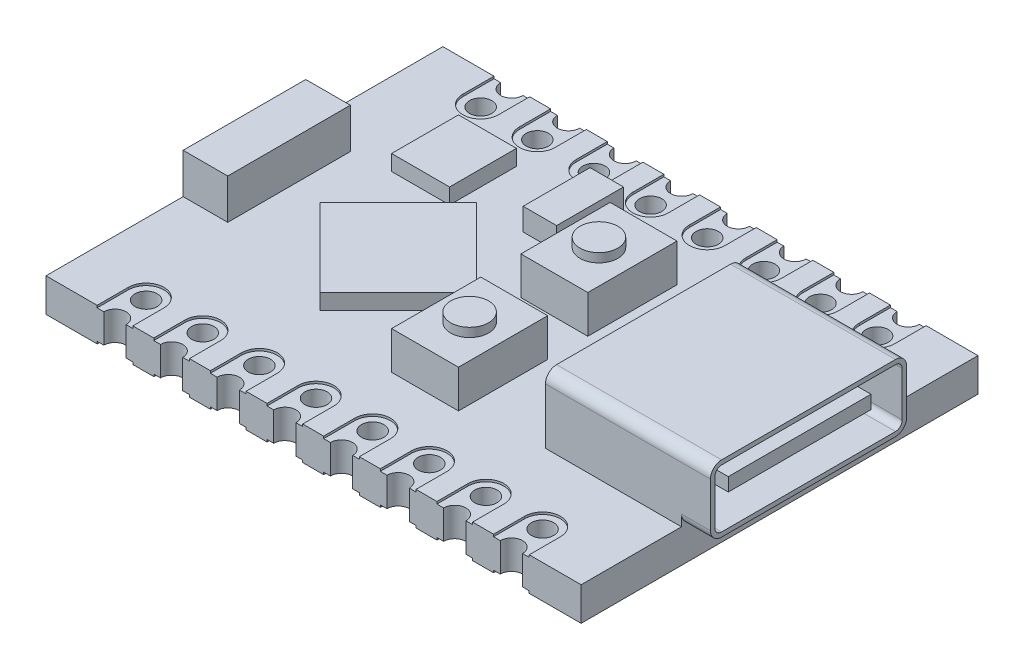
SolidWorks part; units mm, degrees
ref_plane "Front Plane" through (0, 0, 0) normal (0, 0, 1) x (1, 0, 0)
ref_plane "Top Plane" through (0, 0, 0) normal (0, 1, 0) x (1, 0, 0)
ref_plane "Right Plane" through (0, 0, 0) normal (1, 0, 0) x (0, 0, -1)
sketch "Sketch1" plane through (0, 0, 0) normal (0, 1, 0) x (1, 0, 0)
  line L1 (0, 0) -> (24, 0)
  line L2 (0, 0) -> (0, 17.8)
  line L3 (0, 17.8) -> (24, 17.8)
  line L4 (24, 0) -> (24, 17.8)
  dimension "D1" = 24
  dimension "D2" = 17.8
sketch "Sketch2" plane through (0, 0, 0) normal (0, 1, 0) x (1, 0, 0)
  line L0 (0, 0) -> (0, 17.8) construction
  line L1 (0, 0) -> (0, 17.8)
  line L2 (0, 17.8) -> (24, 17.8) construction
  line L3 (0, 17.8) -> (24, 17.8)
  line L4 (24, 0) -> (24, 17.8) construction
  line L5 (24, 0) -> (24, 17.8)
  line L6 (0, 0) -> (24, 0) construction
  line L7 (0, 0) -> (24, 0)
extrude "Boss-Extrude1" add sketch "Sketch2" against normal blind 1.5
sketch "Sketch3" plane through (0, 0, 0) normal (0, 1, 0) x (1, 0, 0)
  line L0 (0, 8.9) -> (24, 8.9) construction
  line L1 (0, 0) -> (0, 17.8) construction
  line L2 (24, 0) -> (24, 17.8) construction
  line L4 (2, 11.65) -> (0, 11.65)
  line L5 (2, 11.65) -> (2, 6.15)
  line L6 (2, 6.15) -> (0, 6.15)
  line L7 (0, 11.65) -> (0, 6.15)
  line L8 (2, 11.65) -> (0, 6.15) construction
  line L9 (2, 6.15) -> (0, 11.65) construction
  point P6 (1, 8.9)
  dimension "D1" = 5.5
  dimension "D2" = 2
extrude "Boss-Extrude2" add sketch "Sketch3" along normal blind 1.8
sketch "Sketch4" plane through (0, 0, 0) normal (0, 1, 0) x (1, 0, 0)
  line L0 (2, 6.15) -> (2, 11.65) construction
  line L3 (4, 8.3) -> (7.5, 11.8)
  line L4 (4, 8.3) -> (7.5, 4.8)
  line L5 (7.5, 11.8) -> (11, 8.3)
  line L6 (7.5, 4.8) -> (11, 8.3)
  line L7 (0, 17.8) -> (24, 17.8) construction
  dimension "D1" = 6
  dimension "D2" = 7
  dimension "D3" = 7
  dimension "D4" = 2
extrude "Boss-Extrude3" add sketch "Sketch4" along normal blind 0.7
sketch "Sketch5" plane through (0, 0, 0) normal (0, 1, 0) x (1, 0, 0)
  line L0 (0, 17.8) -> (24, 17.8) construction
  line L1 (3.7, 14.8) -> (6.3, 14.8)
  line L2 (3.7, 14.8) -> (3.7, 11.8)
  line L3 (3.7, 11.8) -> (6.3, 11.8)
  line L4 (6.3, 14.8) -> (6.3, 11.8)
  line L5 (0, 0) -> (0, 17.8) construction
  dimension "D1" = 2.6
  dimension "D2" = 3
  dimension "D3" = 3
  dimension "D4" = 3.7
extrude "Boss-Extrude4" add sketch "Sketch5" along normal blind 0.7
sketch "Sketch6" plane through (0, 0, 0) normal (0, 1, 0) x (1, 0, 0)
  line L0 (0, 0) -> (0, 17.8) construction
  line L1 (9, 15.4) -> (10.5, 15.4)
  line L2 (9, 15.4) -> (9, 12.4)
  line L3 (9, 12.4) -> (10.5, 12.4)
  line L4 (10.5, 15.4) -> (10.5, 12.4)
  line L5 (0, 17.8) -> (24, 17.8) construction
  dimension "D1" = 1.5
  dimension "D2" = 3
  dimension "D3" = 9
  dimension "D4" = 2.4
extrude "Boss-Extrude5" add sketch "Sketch6" along normal blind 1
sketch "Sketch7" plane through (0, 0, 0) normal (0, 1, 0) x (1, 0, 0)
  line L0 (0, 17.8) -> (24, 17.8) construction
  line L1 (11.5, 13.8) -> (14.5, 13.8)
  line L2 (11.5, 13.8) -> (11.5, 9.8)
  line L3 (11.5, 9.8) -> (14.5, 9.8)
  line L4 (14.5, 13.8) -> (14.5, 9.8)
  line L6 (24, 0) -> (24, 17.8) construction
  dimension "D1" = 3
  dimension "D2" = 4
  dimension "D3" = 4
  dimension "D4" = 9.5
extrude "Boss-Extrude6" add sketch "Sketch7" along normal blind 1.7
sketch "Sketch8" plane through (0, 1.7, 0) normal (0, 1, 0) x (1, 0, 0)
  line L0 (13, 11.8) -> (13, 13.8) construction
  line L1 (14.5, 13.8) -> (11.5, 13.8) construction
  line L2 (13, 11.8) -> (11.5, 11.8) construction
  line L3 (11.5, 13.8) -> (11.5, 9.8) construction
  circle A0 centre (13, 11.8) radius 0.85
  dimension "D1" = 1.7
extrude "Boss-Extrude7" add sketch "Sketch8" along normal blind 0.4
ref_plane "Plane1" through (0, 0, -8.9) normal (0, 0, -1) x (-1, 0, 0)
mirror "Mirror1" about plane through (0, 0, -8.9) normal (0, 0, -1) of "Boss-Extrude7", "Boss-Extrude6"
sketch "Sketch9" plane through (0, 0, 0) normal (0, 1, 0) x (1, 0, 0)
  line L0 (3.0931, 16.4027) -> (0, 16.4027) construction
  line L1 (0, 0) -> (0, 17.8) construction
  line L2 (0, 16.4027) -> (24, 16.4027) construction
  line L3 (24, 0) -> (24, 17.8) construction
  circle A0 centre (3.0931, 16.4027) radius 0.5
  circle A1 centre (5.6331, 16.4027) radius 0.5
  circle A2 centre (8.1731, 16.4027) radius 0.5
  circle A3 centre (10.7131, 16.4027) radius 0.5
  circle A4 centre (13.2531, 16.4027) radius 0.5
  circle A5 centre (15.7931, 16.4027) radius 0.5
  circle A6 centre (18.3331, 16.4027) radius 0.5
  circle A7 centre (20.8731, 16.4027) radius 0.5
  dimension "D1" = 1
  dimension "D2" = 8
extrude "Cut-Extrude1" cut sketch "Sketch9" against normal through all
sketch "Sketch10" plane through (0, 0, 0) normal (0, 1, 0) x (1, 0, 0)
  line L0 (2.2931, 16.4027) -> (2.2931, 17.8)
  line L1 (0, 17.8) -> (24, 17.8) construction
  line L2 (3.8931, 16.4027) -> (3.8931, 17.8)
  line L3 (3.8931, 17.8) -> (2.2931, 17.8)
  circle A0 centre (3.0931, 16.4027) radius 0.5 construction
  circle A1 centre (3.0931, 16.4027) radius 0.5 construction
  arc A2 (2.2931, 16.4027) -> (3.8931, 16.4027) centre (3.0931, 16.4027) ccw
  circle A3 centre (3.0931, 17.8) radius 0.5 construction
  circle A4 centre (3.0931, 16.4027) radius 0.8 construction
  dimension "D2" = 1
  dimension "D1" = 0.3
extrude "Cut-Extrude2" cut sketch "Sketch10" against normal blind 0.1
pattern_linear "LPattern1" count 8 spacing 2.54 along (1, 0, 0) of "Cut-Extrude2"
sketch "Sketch11" plane through (0, 0, 0) normal (0, 1, 0) x (1, 0, 0)
  circle A0 centre (3.0931, 17.8) radius 0.5 construction
  circle A1 centre (3.0931, 17.8) radius 0.5
  circle A2 centre (5.6331, 17.8) radius 0.5
  circle A3 centre (8.1731, 17.8) radius 0.5
  circle A4 centre (10.7131, 17.8) radius 0.5
  circle A5 centre (13.2531, 17.8) radius 0.5
  circle A6 centre (15.7931, 17.8) radius 0.5
  circle A7 centre (18.3331, 17.8) radius 0.5
  circle A8 centre (20.8731, 17.8) radius 0.5
  dimension "D1" = 8
extrude "Cut-Extrude3" cut sketch "Sketch11" against normal through all
ref_plane "Plane2" through (0, -0.75, 0) normal (0, 1, 0) x (1, 0, 0)
mirror "Mirror2" about plane through (0, -0.75, 0) normal (0, 1, 0) of "LPattern1", "Cut-Extrude2"
mirror "Mirror3" about plane through (0, 0, -8.9) normal (0, 0, -1) of "Cut-Extrude3", "Mirror2", "LPattern1", "Cut-Extrude2", "Cut-Extrude1"
ref_plane "Plane3" through (25.3, 0, 0) normal (1, 0, 0) x (0, 0, -1)
sketch "Sketch12" plane through (25.3, 0, 0) normal (1, 0, 0) x (0, 0, -1)
  line L0 (8.9, 0) -> (8.9, 3) construction
  line L1 (0, 0) -> (17.8, 0) construction
  line L2 (4.5, 1.5) -> (13.3, 1.5) construction
  line L4 (4.5, 3) -> (13.3, 3)
  line L5 (4.5, 3) -> (4.5, 0)
  line L6 (4.5, 0) -> (13.3, 0)
  line L7 (13.3, 3) -> (13.3, 0)
  line L8 (4.5, 3) -> (13.3, 0) construction
  line L9 (4.5, 0) -> (13.3, 3) construction
  point P4 (8.9, 1.5)
  point P7 (8.9, 1.5)
  dimension "D1" = 3
  dimension "D2" = 8.8
extrude "Boss-Extrude8" add sketch "Sketch12" against normal blind 7.4
fillet "Fillet1" radius 0.5 4 edges at (24.65, 0, -4.5) (24.65, 0, -13.3) (21.6, 3, -13.3) (21.6, 3, -4.5)
sketch "Sketch13" plane through (25.3, 0, 0) normal (1, 0, 0) x (0, 0, -1)
  line L0 (4.7, 2.5) -> (4.7, 0.5)
  line L1 (5, 0.2) -> (12.8, 0.2)
  line L2 (13.1, 0.5) -> (13.1, 2.5)
  line L3 (12.8, 2.8) -> (5, 2.8)
  line L4 (4.5, 2.5) -> (4.5, 0.5)
  line L5 (5, 0) -> (12.8, 0)
  line L6 (13.3, 0.5) -> (13.3, 2.5)
  line L7 (12.8, 3) -> (5, 3)
  line L8 (4.5, 2.5) -> (4.5, 0.5)
  line L9 (5, 0) -> (12.8, 0)
  line L10 (13.3, 0.5) -> (13.3, 2.5)
  line L11 (12.8, 3) -> (5, 3)
  arc A0 (5, 2.8) -> (4.7, 2.5) centre (5, 2.5) ccw
  arc A1 (4.7, 0.5) -> (5, 0.2) centre (5, 0.5) ccw
  arc A2 (12.8, 0.2) -> (13.1, 0.5) centre (12.8, 0.5) ccw
  arc A3 (13.1, 2.5) -> (12.8, 2.8) centre (12.8, 2.5) ccw
  arc A4 (4.5, 0.5) -> (5, 0) centre (5, 0.5) ccw
  arc A5 (12.8, 0) -> (13.3, 0.5) centre (12.8, 0.5) ccw
  arc A6 (13.3, 2.5) -> (12.8, 3) centre (12.8, 2.5) ccw
  arc A7 (5, 3) -> (4.5, 2.5) centre (5, 2.5) ccw
  arc A8 (4.5, 0.5) -> (5, 0) centre (5, 0.5) ccw
  arc A9 (12.8, 0) -> (13.3, 0.5) centre (12.8, 0.5) ccw
  arc A10 (13.3, 2.5) -> (12.8, 3) centre (12.8, 2.5) ccw
  arc A11 (5, 3) -> (4.5, 2.5) centre (5, 2.5) ccw
  dimension "D1" = 0
  dimension "D2" = 0.2
extrude "Cut-Extrude4" cut sketch "Sketch13" against normal blind 6.4 contours L2 A3 L3 A0 L0 A1 L1 A2
sketch "Sketch14" plane through (18.9, 0, 0) normal (1, 0, 0) x (0, 0, -1)
  line L0 (5.7, 1.8) -> (5.7, 1.2)
  line L1 (5.7, 1.2) -> (12.1, 1.2)
  line L2 (12.1, 1.2) -> (12.1, 1.8)
  line L3 (12.1, 1.8) -> (5.7, 1.8)
  line L4 (13.1, 0.5) -> (13.1, 2.5)
  line L5 (12.8, 2.8) -> (5, 2.8)
  line L6 (4.7, 2.5) -> (4.7, 0.5)
  line L7 (5, 0.2) -> (12.8, 0.2)
  line L8 (13.1, 0.5) -> (13.1, 2.5)
  line L9 (12.8, 2.8) -> (5, 2.8)
  line L10 (4.7, 2.5) -> (4.7, 0.5)
  line L11 (5, 0.2) -> (12.8, 0.2)
  arc A0 (5.7, 1.8) -> (5.7, 1.8) centre (5.7, 1.8) ccw
  arc A1 (5.7, 1.2) -> (5.7, 1.2) centre (5.7, 1.2) ccw
  arc A2 (12.1, 1.2) -> (12.1, 1.2) centre (12.1, 1.2) ccw
  arc A3 (12.1, 1.8) -> (12.1, 1.8) centre (12.1, 1.8) ccw
  arc A4 (13.1, 2.5) -> (12.8, 2.8) centre (12.8, 2.5) ccw
  arc A5 (5, 2.8) -> (4.7, 2.5) centre (5, 2.5) ccw
  arc A6 (4.7, 0.5) -> (5, 0.2) centre (5, 0.5) ccw
  arc A7 (12.8, 0.2) -> (13.1, 0.5) centre (12.8, 0.5) ccw
  arc A8 (13.1, 2.5) -> (12.8, 2.8) centre (12.8, 2.5) ccw
  arc A9 (5, 2.8) -> (4.7, 2.5) centre (5, 2.5) ccw
  arc A10 (4.7, 0.5) -> (5, 0.2) centre (5, 0.5) ccw
  arc A11 (12.8, 0.2) -> (13.1, 0.5) centre (12.8, 0.5) ccw
  dimension "D1" = 0
  dimension "D2" = 1
extrude "Boss-Extrude9" add sketch "Sketch14" along normal blind 6 contours L2 L3 L0 L1
sketch "Sketch15" plane through (0, 0, 0) normal (-1, 0, 0) x (0, 0, 1)
  line L0 (-6.15, 1.8) -> (-6.15, 0) construction
  line L1 (-11.65, 0) -> (-6.15, 0)
  line L2 (-11.65, 0) -> (-11.65, 0.01)
  line L3 (-11.65, 0.01) -> (-6.15, 0.01)
  line L4 (-6.15, 0) -> (-6.15, 0.01)
  dimension "D1" = 0.01
extrude "Cut-Extrude5" cut sketch "Sketch15" against normal blind 0.01
